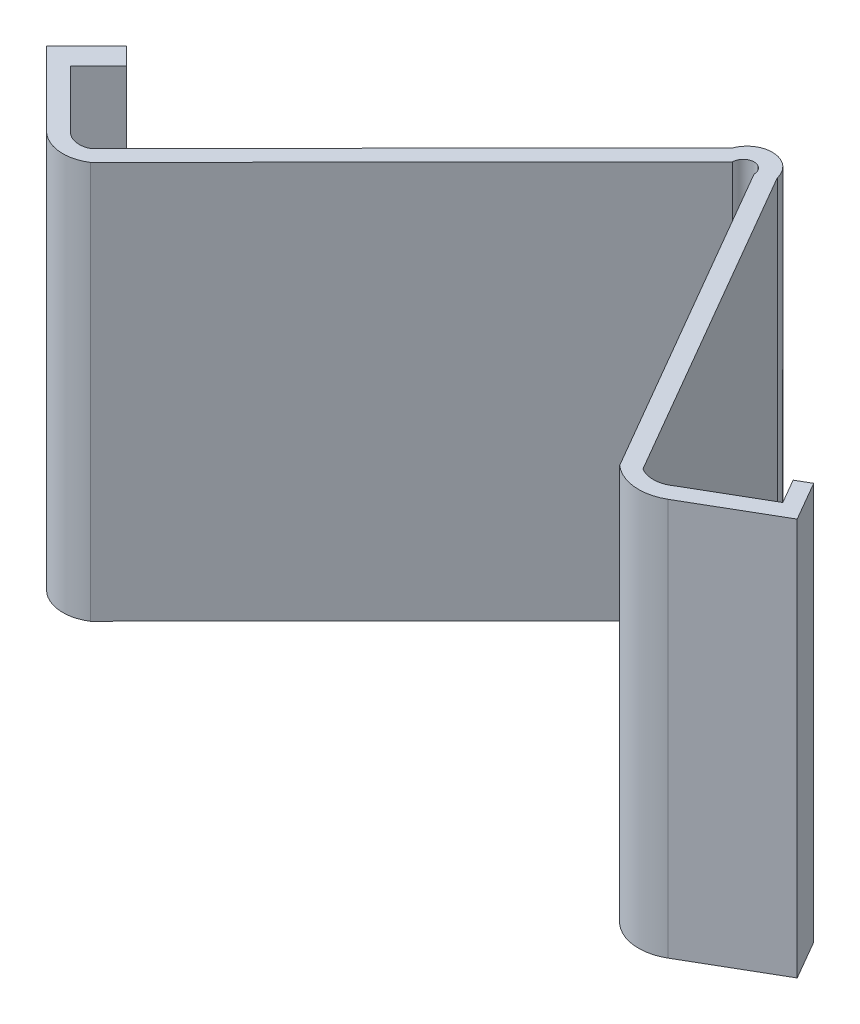
SolidWorks part; units mm, degrees
ref_plane "前基準面" through (0, 0, 0) normal (0, 0, 1) x (1, 0, 0)
ref_plane "上基準面" through (0, 0, 0) normal (0, 1, 0) x (1, 0, 0)
ref_plane "右基準面" through (0, 0, 0) normal (1, 0, 0) x (0, 0, -1)
sketch "草圖1" plane through (0, 0, 0) normal (0, 1, 0) x (1, 0, 0)
  line L0 (-45.4878, -38.6148) -> (10.9966, 18.0377)
  line L1 (-45.4878, -38.6148) -> (-43.3634, -40.733)
  line L2 (10.9966, 18.0377) -> (13.1211, 15.9196)
  line L3 (-43.3634, -40.733) -> (13.1211, 15.9196)
  line L4 (16.8986, 15.9196) -> (49.4822, -40.3237)
  line L5 (16.8986, 15.9196) -> (19.4945, 17.4234)
  line L6 (49.4822, -40.3237) -> (52.0781, -38.8199)
  line L7 (19.4945, 17.4234) -> (52.0781, -38.8199)
  line L8 (13.1211, 15.9196) -> (16.8986, 15.9196)
  line L9 (-52.0067, -39.7967) -> (-49.8886, -37.6722)
  line L10 (-52.0067, -39.7967) -> (-61.9209, -29.9119)
  line L11 (-49.8886, -37.6722) -> (-59.8028, -27.7874)
  line L12 (-61.9209, -29.9119) -> (-59.8028, -27.7874)
  line L17 (57.4, -38.6427) -> (69.514, -31.6247)
  line L18 (57.4, -38.6427) -> (58.9039, -41.2386)
  line L19 (69.514, -31.6247) -> (71.0178, -34.2206)
  line L20 (58.9039, -41.2386) -> (71.0178, -34.2206)
  line L21 (-61.9209, -29.9119) -> (-54.8604, -22.8303)
  line L22 (-61.9209, -29.9119) -> (-64.9803, -26.8617)
  line L23 (-54.8604, -22.8303) -> (-57.9197, -19.7801)
  line L24 (-64.9803, -26.8617) -> (-57.9197, -19.7801)
  line L25 (71.0178, -34.2206) -> (73.3147, -32.8899)
  line L26 (71.0178, -34.2206) -> (67.0075, -27.2983)
  line L27 (73.3147, -32.8899) -> (69.3044, -25.9677)
  line L28 (67.0075, -27.2983) -> (69.3044, -25.9677)
  arc A0 (18.3722, 13.3761) -> (11.3477, 14.141) centre (15.1528, 16.4481) ccw
  arc A1 (16.8986, 15.9196) -> (13.1211, 15.9196) centre (15.0098, 15.9196) ccw
  arc A2 (-43.3634, -40.733) -> (-52.0067, -39.7967) centre (-47.1014, -34.8768) cw
  arc A3 (-49.8886, -37.6722) -> (-45.4878, -38.6148) centre (-47.0796, -35.3018) ccw
  arc A4 (52.0781, -38.8199) -> (57.4, -38.6427) centre (54.6049, -34.7006) ccw
  arc A5 (49.4822, -40.3237) -> (58.9039, -41.2386) centre (54.8313, -34.2087) ccw
  point P24 (0, 0)
  dimension "D12" = 8
  dimension "D1" = 3
  dimension "D2" = 3
  dimension "D3" = 3
  dimension "D4" = 14
  dimension "D5" = 75
  dimension "D6" = 80
  dimension "D7" = 65
  dimension "D8" = 90
  dimension "D9" = 14
  dimension "D10" = 3
  dimension "D11" = 10
  dimension "D13" = 90
extrude "填料-伸長1" add sketch "草圖1" along normal blind 70
